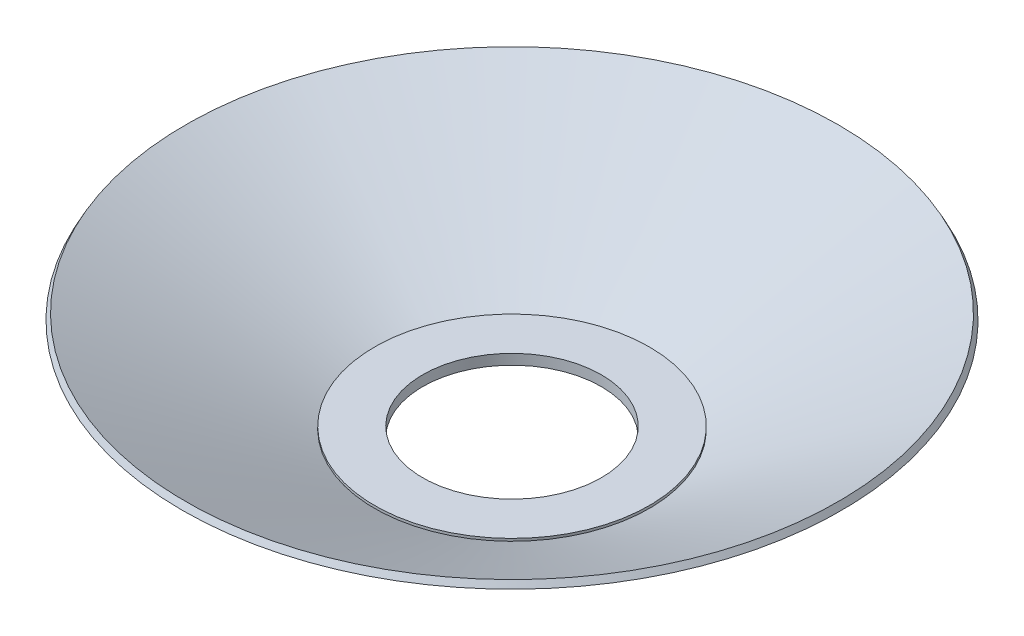
SolidWorks part; units mm, degrees
ref_plane "Спереди" through (0, 0, 0) normal (0, 0, 1) x (1, 0, 0)
ref_plane "Сверху" through (0, 0, 0) normal (0, 1, 0) x (1, 0, 0)
ref_plane "Справа" through (0, 0, 0) normal (1, 0, 0) x (0, 0, -1)
sketch "Эскиз1" plane through (0, 0, 0) normal (0, 0, 1) x (1, 0, 0)
  line L0 (20, -0.3674) -> (47.5, 14.2546)
  line L1 (47.5, 14.2546) -> (47.9695, 13.3716)
  line L2 (47.9695, 13.3716) -> (20, -1.5)
  line L3 (20, -1.5) -> (13, -1.5)
  line L4 (13, -1.5) -> (13, 0)
  line L5 (13, 0) -> (20, 0)
  line L6 (20, 0) -> (20, -0.3674)
  line L7 (0, 0) -> (0, 14.2546) construction
  line L8 (0, 14.2546) -> (47.5, 14.2546) construction
  dimension "D1" = 28
  dimension "D2" = 47.5
  dimension "D3" = 20
  dimension "D4" = 1
  dimension "D5" = 1.5
  dimension "D6" = 7
revolve "Повернуть1" add sketch "Эскиз1" angle 360 about L7
